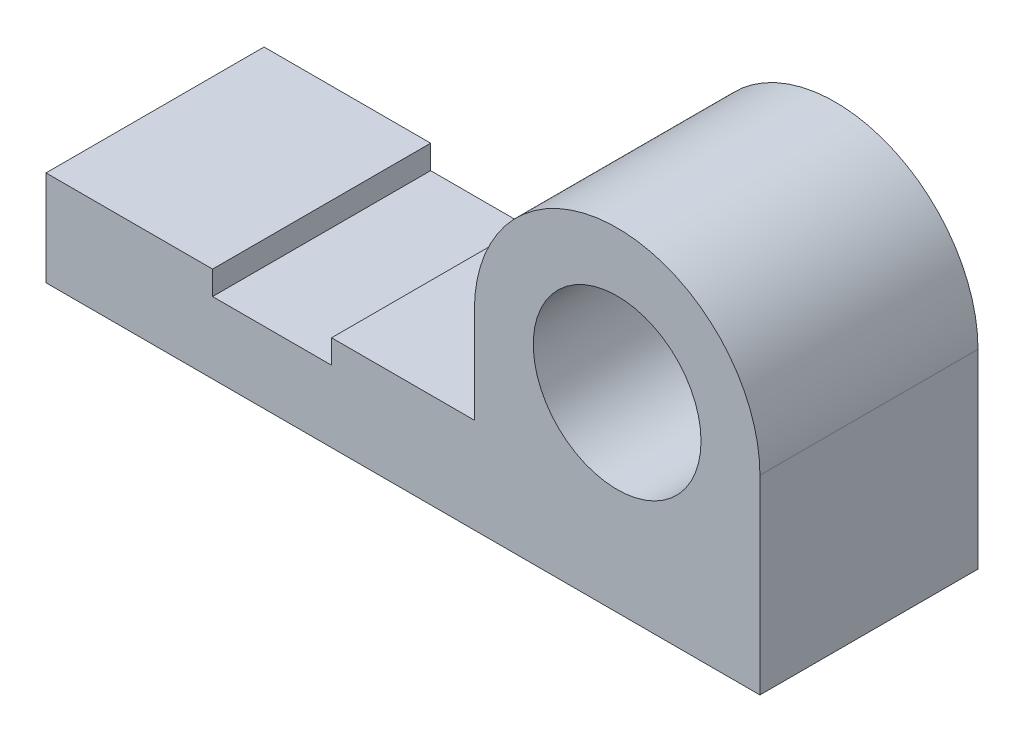
SolidWorks part; units mm, degrees
ref_plane "Front Plane" through (0, 0, 0) normal (0, 0, 1) x (1, 0, 0)
ref_plane "Top Plane" through (0, 0, 0) normal (0, 1, 0) x (1, 0, 0)
ref_plane "Right Plane" through (0, 0, 0) normal (1, 0, 0) x (0, 0, -1)
sketch "Sketch2" plane through (0, 0, 0) normal (0, 0, 1) x (1, 0, 0)
  line L0 (0, 0) -> (-127.6877, 0)
  line L1 (-127.6877, 0) -> (-127.6877, 17.025)
  line L2 (-127.6877, 17.025) -> (-97.8939, 17.025)
  line L3 (-97.8939, 17.025) -> (-97.8939, 12.7688)
  line L4 (-97.8939, 12.7688) -> (-76.6126, 12.7688)
  line L5 (-76.6126, 12.7688) -> (-76.6126, 17.025)
  line L6 (-76.6126, 17.025) -> (-51.0751, 17.025)
  line L7 (-51.0751, 17.025) -> (-51.0751, 34.0501)
  line L8 (0, 0) -> (0, 34.0501)
  arc A0 (0, 34.0501) -> (-51.0751, 34.0501) centre (-25.5375, 34.0501) ccw
  circle A1 centre (-25.5375, 34.0501) radius 15
  dimension "D1" = 30
extrude "Boss-Extrude1" add sketch "Sketch2" along normal blind 39
